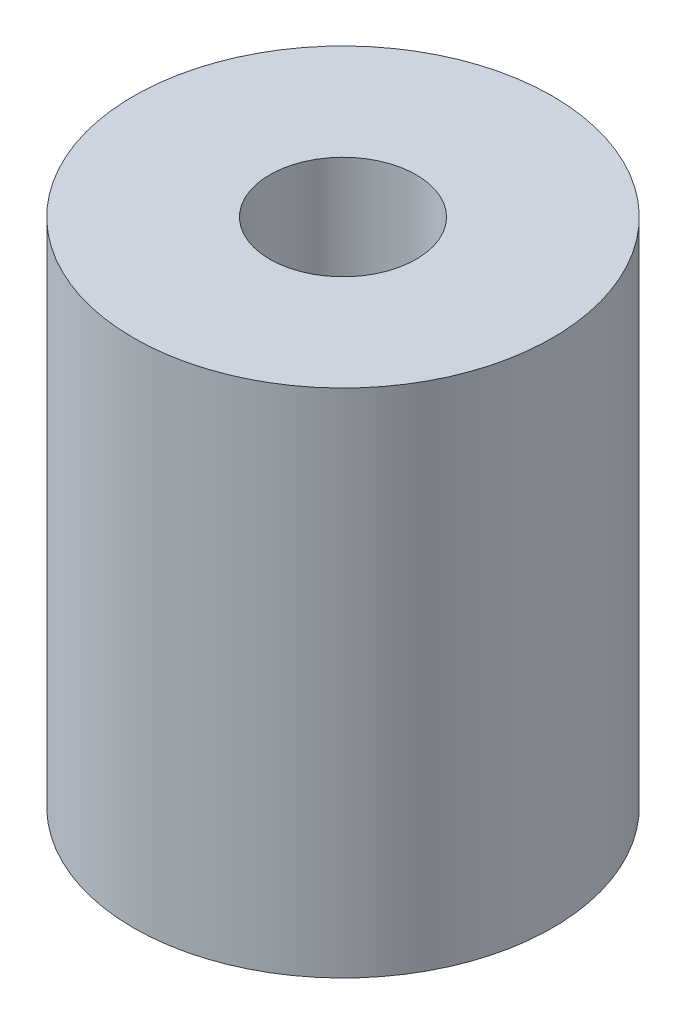
SolidWorks part; units mm, degrees
ref_plane "Front Plane" through (0, 0, 0) normal (0, 0, 1) x (1, 0, 0)
ref_plane "Top Plane" through (0, 0, 0) normal (0, 1, 0) x (1, 0, 0)
ref_plane "Right Plane" through (0, 0, 0) normal (1, 0, 0) x (0, 0, -1)
sketch "Sketch1" plane through (0, 0, 0) normal (0, 1, 0) x (1, 0, 0)
  circle A0 centre (0, 0) radius 2.15
  circle A1 centre (0, 0) radius 6.15
  dimension "D1" = 4.3
  dimension "D2" = 4
extrude "Boss-Extrude1" add sketch "Sketch1" along normal blind 15
